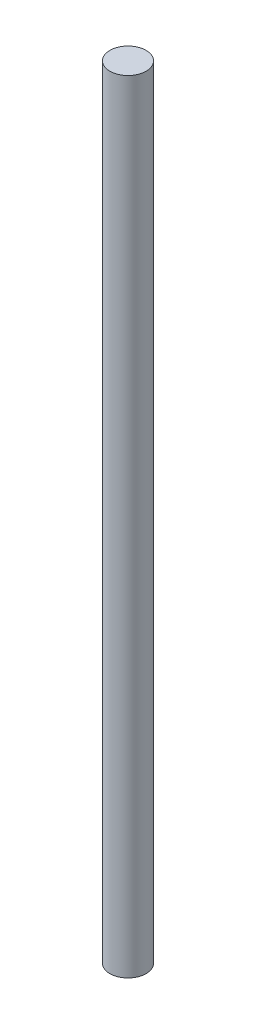
SolidWorks part; units mm, degrees
ref_plane "前视基准面" through (0, 0, 0) normal (0, 0, 1) x (1, 0, 0)
ref_plane "上视基准面" through (0, 0, 0) normal (0, 1, 0) x (1, 0, 0)
ref_plane "右视基准面" through (0, 0, 0) normal (1, 0, 0) x (0, 0, -1)
sketch "草图1" plane through (0, 0, 0) normal (0, 1, 0) x (1, 0, 0)
  circle A0 centre (0, 0) radius 1.75
  circle A1 centre (0, 0) radius 1.75 construction
  dimension "D1" = 3.5
extrude "凸台-拉伸1" add sketch "草图1" along normal blind 75.6
